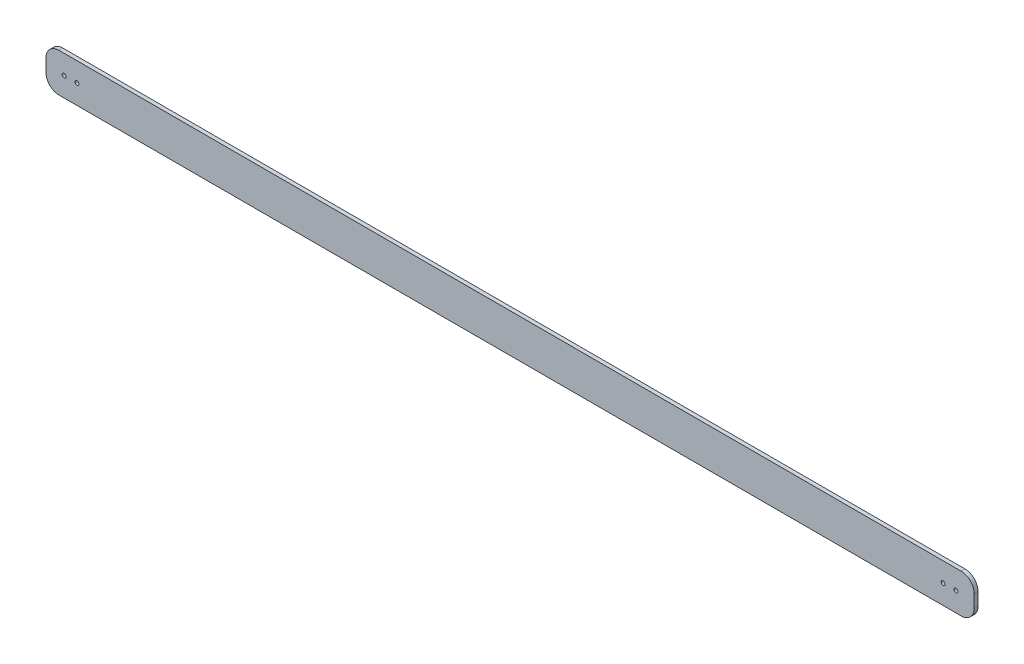
SolidWorks part; units mm, degrees
ref_plane "Plan de face" through (0, 0, 0) normal (0, 0, 1) x (1, 0, 0)
ref_plane "Plan de dessus" through (0, 0, 0) normal (0, 1, 0) x (1, 0, 0)
ref_plane "Plan de droite" through (0, 0, 0) normal (1, 0, 0) x (0, 0, -1)
sketch "Sketch1" plane through (0, 0, 0) normal (0, 0, 1) x (1, 0, 0)
  line L0 (-306.8169, 113.8649) -> (411.1831, 113.8649) construction
  line L1 (-296.8169, 128.8649) -> (401.1831, 128.8649)
  line L2 (-306.8169, 118.8649) -> (-306.8169, 108.8649)
  line L3 (-296.8169, 98.8649) -> (401.1831, 98.8649)
  line L4 (411.1831, 118.8649) -> (411.1831, 108.8649)
  arc A0 (401.1831, 98.8649) -> (411.1831, 108.8649) centre (401.1831, 108.8649) ccw
  arc A1 (401.1831, 128.8649) -> (411.1831, 118.8649) centre (401.1831, 118.8649) cw
  arc A2 (-306.8169, 108.8649) -> (-296.8169, 98.8649) centre (-296.8169, 108.8649) ccw
  arc A3 (-296.8169, 128.8649) -> (-306.8169, 118.8649) centre (-296.8169, 118.8649) ccw
  circle A4 centre (-292.8169, 113.8649) radius 1.5
  circle A5 centre (-282.8169, 113.8649) radius 1.5
  circle A6 centre (387.1831, 113.8649) radius 1.5
  circle A7 centre (397.1831, 113.8649) radius 1.5
  point P6 (411.1831, 98.8649)
  point P9 (411.1831, 128.8649)
  point P14 (-306.8169, 128.8649)
  dimension "D3" = 10
  dimension "D4" = 3
  dimension "D5" = 3
  dimension "D6" = 3
  dimension "D7" = 3
  dimension "D10" = 14
  dimension "D12" = 670
  dimension "D2" = 30
  dimension "D8" = 14
  dimension "D9" = 10
  dimension "D11" = 10
extrude "Boss-Extrude1" add sketch "Sketch1" along normal blind 3
